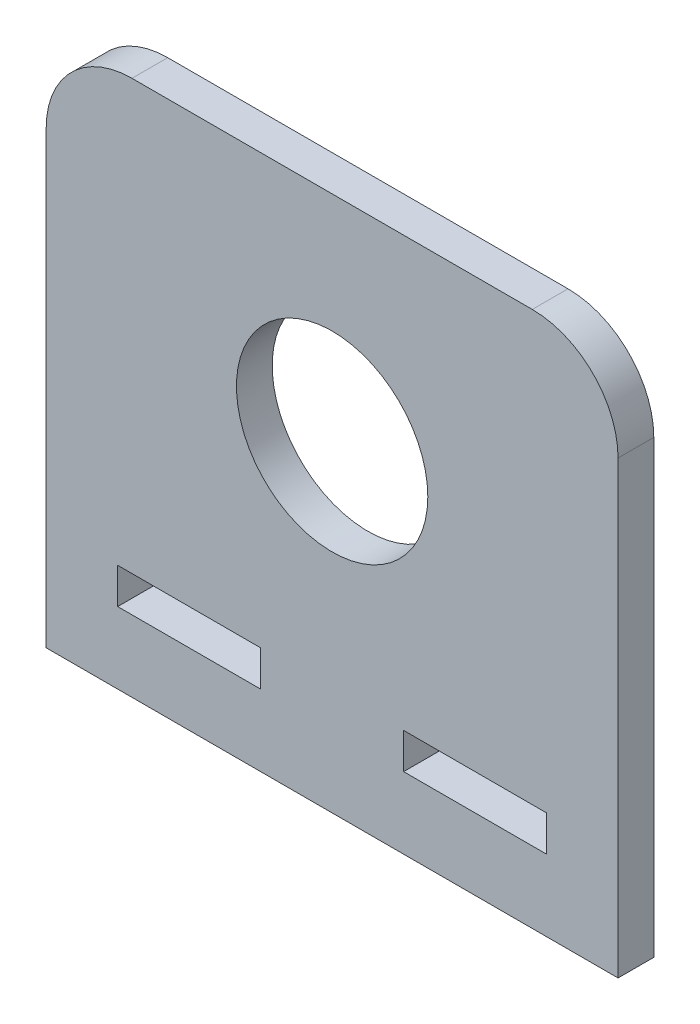
SolidWorks part; units mm, degrees
ref_plane "Front Plane" through (0, 0, 0) normal (0, 0, 1) x (1, 0, 0)
ref_plane "Top Plane" through (0, 0, 0) normal (0, 1, 0) x (1, 0, 0)
ref_plane "Right Plane" through (0, 0, 0) normal (1, 0, 0) x (0, 0, -1)
sketch "Sketch1" plane through (0, 0, 0) normal (0, 0, 1) x (1, 0, 0)
  line L3 (50.8, 0) -> (50.8, 40.005)
  line L4 (43.18, 47.625) -> (7.62, 47.625)
  line L5 (0, 40.005) -> (0, 0)
  line L6 (0, 0) -> (50.8, 0)
  line L8 (25.4, 28.575) -> (25.4, 0) construction
  line L9 (6.35, 6.35) -> (19.05, 6.35)
  line L10 (6.35, 6.35) -> (6.35, 9.525)
  line L11 (6.35, 9.525) -> (19.05, 9.525)
  line L12 (19.05, 6.35) -> (19.05, 9.525)
  line L13 (31.75, 6.35) -> (44.45, 6.35)
  line L14 (31.75, 6.35) -> (31.75, 9.525)
  line L15 (31.75, 9.525) -> (44.45, 9.525)
  line L16 (44.45, 6.35) -> (44.45, 9.525)
  circle A0 centre (25.4, 28.575) radius 8.5
  arc A1 (50.8, 40.005) -> (43.18, 47.625) centre (43.18, 40.005) ccw
  arc A2 (7.62, 47.625) -> (0, 40.005) centre (7.62, 40.005) ccw
  point P15 (50.8, 47.625)
  dimension "D2" = 17
  dimension "D6" = 7.62
  dimension "D1" = 6.35
  dimension "D3" = 12.7
  dimension "D4" = 12.7
  dimension "D5" = 3.175
  dimension "D7" = 6.35
  dimension "D8" = 19.05
  dimension "D9" = 50.8
  dimension "D10" = 19.05
extrude "Boss-Extrude1" add sketch "Sketch1" along normal blind 3.175
